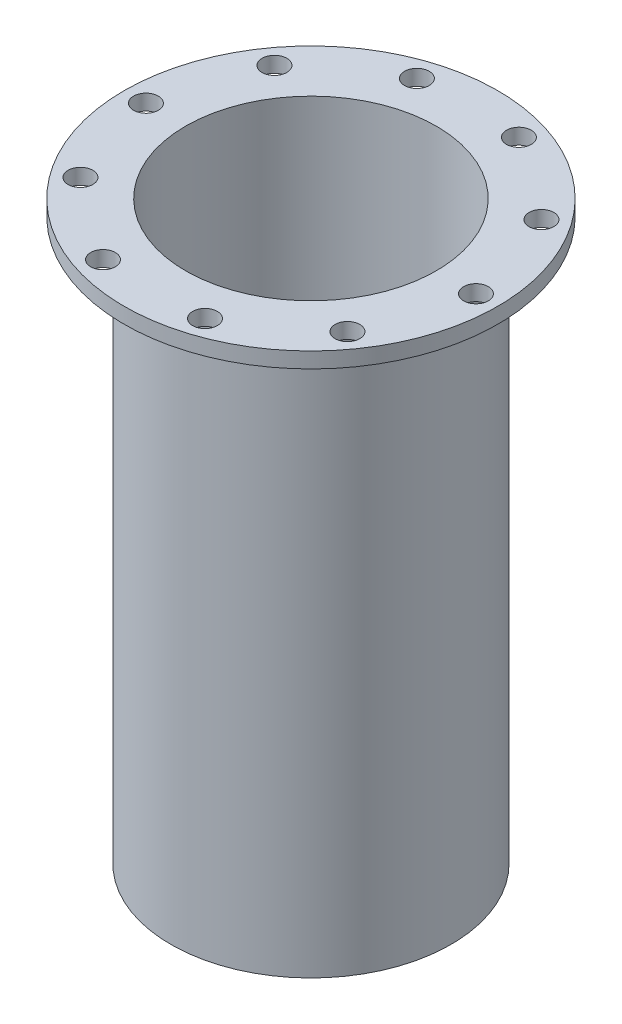
SolidWorks part; units mm, degrees
material "1023 Carbon Steel Sheet (SS)"
ref_plane "Front Plane" through (0, 0, 0) normal (0, 0, 1) x (1, 0, 0)
ref_plane "Top Plane" through (0, 0, 0) normal (0, 1, 0) x (1, 0, 0)
ref_plane "Right Plane" through (0, 0, 0) normal (1, 0, 0) x (0, 0, -1)
sketch "Sketch1" plane through (0, 0, 0) normal (0, 0, 1) x (1, 0, 0)
  line L0 (0, 0) -> (0, -134.8652) construction
  line L1 (51.1302, 0) -> (51.1302, -213.995)
  line L2 (51.1302, -234.95) -> (57.15, -234.95)
  line L3 (57.15, -234.95) -> (57.15, -6.35)
  line L4 (57.15, -6.35) -> (76.2, -6.35)
  line L5 (76.2, -6.35) -> (76.2, 0)
  line L6 (76.2, 0) -> (51.1302, 0)
  line L7 (51.1302, -213.995) -> (53.6702, -213.995)
  line L8 (53.6702, -213.995) -> (53.6702, -217.043)
  line L9 (53.6702, -217.043) -> (51.1302, -217.043)
  line L10 (-50.927, -210.82) -> (50.927, -210.82) construction
  line L11 (51.1302, -217.043) -> (51.1302, -234.95)
  dimension "D1" = 51.1302
  dimension "D2" = 57.15
  dimension "D3" = 76.2
  dimension "D4" = 6.35
  dimension "D5" = 234.95
  dimension "D6" = 3.175
  dimension "D7" = 3.048
  dimension "D8" = 2.54
revolve "Revolve1" add sketch "Sketch1" angle 360 about L0
hole_wizard "Tap Drill for 3/8-16 Tap1" positions "Sketch2" profile "Sketch3" hole size "3/8" standard "ANSI Inch" end condition through all
sketch "Sketch2" plane through (0, 0, 0) normal (0, 1, 0) x (1, 0, 0)
  point P1 (67.31, 0)
  dimension "D1" = 67.31
sketch "Sketch3" plane through (67.31, 0, 0) normal (1, 0, 0) x (0, 0, 1)
  line L0 (0, 0) -> (0, 234.95)
  line L1 (0, 234.95) -> (5.0419, 234.95)
  line L2 (5.0419, 234.95) -> (5.0419, 0)
  line L5 (5.0419, 0) -> (0, 0)
  line L11 (0, -6.35) -> (0, 107.95) construction
  dimension "Thru Hole Dia." = 10.0838
  dimension "Thru Hole Depth" = 234.95
pattern_circular "CirPattern1" count 10 over 360 about axis through (0, 0, 0) along (0, 1, 0) of "Tap Drill for 3/8-16 Tap1"
